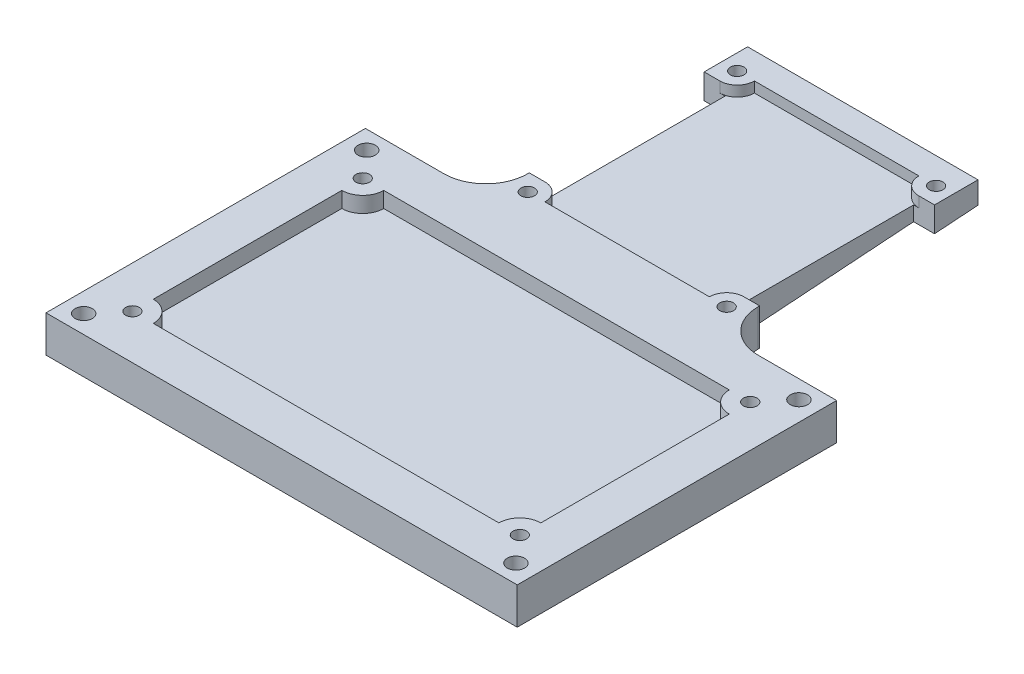
SolidWorks part; units mm, degrees
ref_plane "Front Plane" through (0, 0, 0) normal (0, 0, 1) x (1, 0, 0)
ref_plane "Top Plane" through (0, 0, 0) normal (0, 1, 0) x (1, 0, 0)
ref_plane "Right Plane" through (0, 0, 0) normal (1, 0, 0) x (0, 0, -1)
sketch "Sketch1" plane through (0, 0, 0) normal (0, 1, 0) x (1, 0, 0)
  line L0 (0, 0) -> (90, 0)
  line L1 (90, 0) -> (90, 61)
  line L2 (90, 61) -> (75, 61)
  line L3 (0, 61) -> (0, 0)
  line L4 (86.275, 3.475) -> (86.275, 57.525) construction
  line L5 (86.275, 57.525) -> (3.725, 57.525) construction
  line L6 (15, 61) -> (0, 61)
  line L8 (23, 69) -> (23, 111)
  line L9 (23, 111) -> (67, 111)
  line L10 (67, 69) -> (67, 111)
  line L11 (0, 30.5) -> (90, 30.5) construction
  circle A0 centre (3.725, 57.525) radius 1.65
  circle A1 centre (86.275, 57.525) radius 1.65
  circle A2 centre (86.275, 3.475) radius 1.65
  circle A3 centre (3.725, 3.475) radius 1.65
  arc A4 (15, 61) -> (23, 69) centre (15, 69) ccw
  arc A5 (75, 61) -> (67, 69) centre (75, 69) cw
  point P12 (86.275, 30.5)
  point P13 (90, 30.5)
  point P14 (45, 57.525)
  point P21 (45, 111)
  point P23 (23, 61)
  point P26 (45, 0)
  dimension "D5" = 3.3
  dimension "D6" = 3.3
  dimension "D7" = 3.3
  dimension "D8" = 44
  dimension "D10" = 8
  dimension "D11" = 8
  dimension "D1" = 61
  dimension "D2" = 90
  dimension "D3" = 82.55
  dimension "D4" = 54.05
  dimension "D9" = 50
extrude "Boss-Extrude1" add sketch "Sketch1" along normal blind 7
chamfer "Chamfer1" distance 40 angle 4 1 edges at (45, 0, -111)
sketch "Sketch2" plane through (0, 7, 0) normal (0, 1, 0) x (1, 0, 0)
  line L0 (0, 0) -> (90, 0) construction
  line L1 (8, 52.5) -> (82, 52.5) construction
  line L2 (8, 52.5) -> (8, 8.5) construction
  line L3 (8, 8.5) -> (82, 8.5) construction
  line L4 (82, 52.5) -> (82, 8.5) construction
  line L5 (0, 61) -> (0, 0) construction
  circle A0 centre (8, 52.5) radius 1.3
  circle A1 centre (8, 8.5) radius 1.3
  circle A2 centre (82, 52.5) radius 1.3
  circle A3 centre (82, 8.5) radius 1.3
  point P10 (45, 0)
  point P11 (45, 8.5)
  point P14 (0, 30.5)
  point P15 (8, 30.5)
  dimension "D3" = 2.6
  dimension "D4" = 2.6
  dimension "D5" = 2.6
  dimension "D6" = 2.6
  dimension "D1" = 74
  dimension "D2" = 44
extrude "Cut-Extrude1" cut sketch "Sketch2" against normal through all
sketch "Sketch3" plane through (0, 7, 0) normal (0, 1, 0) x (1, 0, 0)
  line L0 (67, 111) -> (23, 111) construction
  line L1 (26, 106) -> (64, 106) construction
  line L2 (26, 106) -> (26, 66) construction
  line L3 (26, 66) -> (64, 66) construction
  line L4 (64, 106) -> (64, 66) construction
  line L5 (23, 111) -> (23, 69) construction
  circle A0 centre (26, 106) radius 1.3
  circle A1 centre (64, 106) radius 1.3
  circle A2 centre (26, 66) radius 1.3
  circle A3 centre (64, 66) radius 1.3
  dimension "D3" = 5
  dimension "D1" = 40
  dimension "D2" = 38
  dimension "D4" = 3
extrude "Cut-Extrude2" cut sketch "Sketch3" against normal through all
sketch "Sketch4" plane through (0, 7, 0) normal (0, 1, 0) x (1, 0, 0)
  line L1 (12, 52.5) -> (78, 52.5)
  line L2 (8, 48.5) -> (8, 12.5)
  line L3 (12, 8.5) -> (78, 8.5)
  line L4 (82, 48.5) -> (82, 12.5)
  arc A0 (8, 48.5) -> (12, 52.5) centre (8, 52.5) ccw
  arc A1 (78, 52.5) -> (82, 48.5) centre (82, 52.5) ccw
  arc A2 (82, 12.5) -> (78, 8.5) centre (82, 8.5) ccw
  arc A3 (12, 8.5) -> (8, 12.5) centre (8, 8.5) ccw
extrude "Cut-Extrude3" cut sketch "Sketch4" against normal blind 3
sketch "Sketch5" plane through (0, 7, 0) normal (0, 1, 0) x (1, 0, 0)
  line L0 (29.3, 106) -> (60.7, 106)
  line L5 (45, 106) -> (45, 71.9475) construction
  line L6 (20.5, 86) -> (57.0983, 86) construction
  line L7 (26, 102.7) -> (26, 69.3)
  line L8 (64, 102.7) -> (64, 69.3)
  line L9 (29.3, 66) -> (60.7, 66)
  circle A4 centre (26, 106) radius 1.3 construction
  arc A5 (26, 102.7) -> (29.3, 106) centre (26, 106) ccw
  circle A6 centre (26, 66) radius 1.3 construction
  circle A7 centre (64, 106) radius 1.3 construction
  arc A8 (26, 69.3) -> (29.3, 66) centre (26, 66) cw
  arc A9 (60.7, 66) -> (64, 69.3) centre (64, 66) cw
  arc A10 (64, 102.7) -> (60.7, 106) centre (64, 106) cw
  point P24 (26, 86)
  point P25 (45, 106)
  dimension "D1" = 3.3
  dimension "D2" = 3.3
  dimension "D3" = 3.3
  dimension "D4" = 3.3
extrude "Cut-Extrude4" cut sketch "Sketch5" against normal blind 2
sketch "Sketch6" plane through (0, 7, 0) normal (0, 1, 0) x (1, 0, 0)
  line L0 (23, 111) -> (23, 69) construction
  line L1 (27, 102.7) -> (23, 102.7)
  line L2 (27, 102.7) -> (27, 69.3)
  line L3 (27, 69.3) -> (23, 69.3)
  line L4 (23, 102.7) -> (23, 69.3)
  line L5 (45, 106) -> (45, 66) construction
  line L6 (60.7, 106) -> (29.3, 106) construction
  line L7 (29.3, 66) -> (60.7, 66) construction
  line L8 (63, 69.3) -> (67, 69.3)
  line L9 (67, 102.7) -> (67, 69.3)
  line L10 (63, 102.7) -> (67, 102.7)
  line L11 (63, 102.7) -> (63, 69.3)
  dimension "D1" = 4
extrude "Cut-Extrude5" cut sketch "Sketch6" against normal through all
equation "\"D4@Sketch2\"=\"D3@Sketch2\""
equation "\"D5@Sketch2\"=\"D3@Sketch2\""
equation "\"D6@Sketch2\"=\"D3@Sketch2\""
